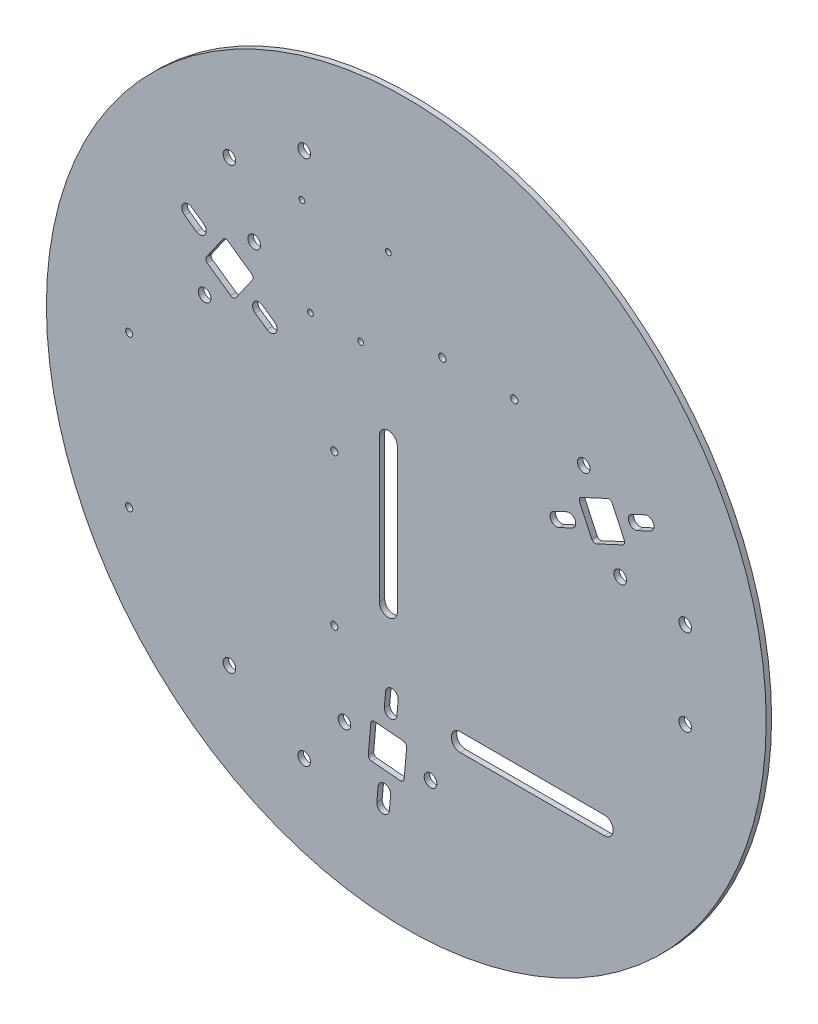
SolidWorks part; units mm, degrees
ref_plane "Front Plane" through (0, 0, 0) normal (0, 0, 1) x (1, 0, 0)
ref_plane "Top Plane" through (0, 0, 0) normal (0, 1, 0) x (1, 0, 0)
ref_plane "Right Plane" through (0, 0, 0) normal (1, 0, 0) x (0, 0, -1)
sketch "Sketch1" plane through (0, 0, 0) normal (0, 0, 1) x (1, 0, 0)
  line L0 (0, 0) -> (-173.2051, 100) construction
  line L1 (0, 0) -> (173.2051, 100) construction
  line L2 (0, 0) -> (0, -200) construction
  line L3 (0, 0) -> (0, 200) construction
  circle A0 centre (0, 0) radius 200
  dimension "D1" = 400
  dimension "D2" = 120
  dimension "D3" = 120
extrude "Boss-Extrude2" add sketch "Sketch1" along normal blind 3
sketch "Sketch9" plane through (0, 0, 3) normal (0, 0, 1) x (1, 0, 0)
  line L0 (0, 0) -> (0, 183.2614) construction
  line L1 (-98.2846, 122.2339) -> (-56.7154, 146.2339) construction
  line L2 (0, 0) -> (-115, 199.1858) construction
  circle A2 centre (-56.7154, 146.2339) radius 3.5
  circle A5 centre (-98.2846, 122.2339) radius 3.5
  point P4 (-77.5, 134.2339)
  dimension "D3" = 7
  dimension "D2" = 24
  dimension "D4" = 155
  dimension "D11" = 30
extrude "Cut-Extrude8" cut sketch "Sketch9" against normal up to surface (3 mm away) up to face at (200, 0, 0)
pattern_circular "CirPattern5" count 3 over 360 about axis through (0, 0, 0) along (0, 0, 1) of "Cut-Extrude8"
sketch "Sketch15" plane through (0, 0, 3) normal (0, 0, 1) x (1, 0, 0)
  line L0 (0, 0) -> (383.7878, 0) construction
  circle A0 centre (20, 85) radius 2
  circle A1 centre (60, 85) radius 2
  dimension "D1" = 4
  dimension "D2" = 4
  dimension "D3" = 40
  dimension "D4" = 85
  dimension "D5" = 20
extrude "Cut-Extrude13" cut sketch "Sketch15" against normal up to surface (3 mm away) up to face at (-53.2154, -146.2339, 0)
sketch "Sketch17" plane through (0, 0, 3) normal (0, 0, 1) x (1, 0, 0)
  line L0 (0, 0) -> (0, 260.2561) construction
  line L1 (0, 0) -> (-189.8731, 132.9506) construction
  line L3 (-112.2255, 66.3734) -> (-95.8425, 54.9019)
  line L5 (-100.754, 82.7565) -> (-84.371, 71.2849)
  line L6 (-112.2255, 66.3734) -> (-100.754, 82.7565)
  line L7 (-95.8425, 54.9019) -> (-84.371, 71.2849)
  line L8 (-81.9152, 57.3576) -> (-75.362, 52.769) construction
  line L9 (-79.9077, 60.2247) -> (-73.3545, 55.6361)
  line L10 (-83.9227, 54.4906) -> (-77.3695, 49.902)
  line L11 (-104.034, 60.6377) -> (-90.1792, 80.4244) construction
  line L12 (-114.6813, 80.3007) -> (-121.2345, 84.8893) construction
  line L13 (-112.6738, 83.1677) -> (-119.227, 87.7563)
  line L14 (-116.6888, 77.4337) -> (-123.242, 82.0223)
  arc A0 (-79.9077, 60.2247) -> (-83.9227, 54.4906) centre (-81.9152, 57.3576) ccw
  arc A1 (-77.3695, 49.902) -> (-73.3545, 55.6361) centre (-75.362, 52.769) ccw
  circle A2 centre (-84.5324, 88.4888) radius 3.5
  circle A3 centre (-112.0641, 49.1695) radius 3.5
  arc A4 (-112.6738, 83.1677) -> (-116.6888, 77.4337) centre (-114.6813, 80.3007) cw
  arc A5 (-123.242, 82.0223) -> (-119.227, 87.7563) centre (-121.2345, 84.8893) cw
  circle A6 centre (-56.7154, 146.2339) radius 3.5 construction
  circle A7 centre (-98.2846, 122.2339) radius 3.5 construction
  circle A8 centre (-56.7154, 146.2339) radius 3.5
  circle A9 centre (-98.2846, 122.2339) radius 3.5
  point P7 (-78.6386, 55.0633)
  point P17 (-80.6461, 52.1963)
  point P24 (-117.9579, 82.595)
  dimension "D9" = 7
  dimension "D1" = 20
  dimension "D2" = 20
  dimension "D3" = 20
  dimension "D4" = 55
  dimension "D5" = 110
  dimension "D6" = 7
  dimension "D7" = 8
  dimension "D8" = 10
  dimension "D10" = 14
  dimension "D11" = 10
extrude "Cut-Extrude15" cut sketch "Sketch17" against normal up to surface (3 mm away) up to face at (22, 85, 0)
pattern_circular "CirPattern7" count 3 over 360 about axis through (0, 0, 0) along (0, 0, 1) of "Cut-Extrude15"
sketch "Sketch18" plane through (0, 0, 3) normal (0, 0, 1) x (1, 0, 0)
  line L0 (-10, 30) -> (-10, -50) construction
  line L1 (-5, 30) -> (-5, -50)
  line L2 (-15, 30) -> (-15, -50)
  arc A0 (-5, 30) -> (-15, 30) centre (-10, 30) ccw
  arc A1 (-15, -50) -> (-5, -50) centre (-10, -50) ccw
  point P2 (-10, -10)
  dimension "D1" = 10
  dimension "D2" = 10
  dimension "D3" = 80
  dimension "D4" = 5
extrude "Cut-Extrude16" cut sketch "Sketch18" against normal up to surface (3 mm away) up to face at (-8.367, -95.6347, 0)
sketch "Sketch19" plane through (0, 0, 3) normal (0, 0, 1) x (1, 0, 0)
  line L0 (0, 0) -> (269.2588, 0) construction
  line L1 (30, -95) -> (110, -95) construction
  line L2 (30, -90) -> (110, -90)
  line L3 (30, -100) -> (110, -100)
  arc A0 (30, -90) -> (30, -100) centre (30, -95) ccw
  arc A1 (110, -100) -> (110, -90) centre (110, -95) ccw
  point P5 (70, -95)
  dimension "D1" = 10
  dimension "D2" = 80
  dimension "D3" = 95
  dimension "D4" = 30
extrude "Cut-Extrude17" cut sketch "Sketch19" against normal up to surface (3 mm away) up to face at (-10, -10, 0)
sketch "Sketch20" plane through (0, 0, 3) normal (0, 0, 1) x (1, 0, 0)
  circle A0 centre (-57.9874, 121.9) radius 1.6
  circle A1 centre (-10, 120.8) radius 1.6
  circle A2 centre (-53.2874, 70) radius 1.6
  circle A3 centre (-25.3874, 70) radius 1.6
  circle A4 centre (20, 85) radius 2 construction
  dimension "D1" = 3.2
  dimension "D2" = 3.2
  dimension "D3" = 3.2
  dimension "D4" = 3.2
  dimension "D5" = 48
  dimension "D6" = 27.9
  dimension "D7" = 4.7
  dimension "D8" = 51.9
  dimension "D9" = 70
  dimension "D10" = 30
  dimension "D11" = 50.8
extrude "Cut-Extrude18" cut sketch "Sketch20" against normal up to surface (3 mm away) up to face at (70, -95, 0)
fillet "Fillet1" radius 2 12 edges at (113.5938, 64.0035, 1.5) (122.0462, 45.8773, 1.5) (95.4677, 55.5511, 1.5) (103.92, 37.4249, 1.5) (-19.5491, -108.7099, 1.5) (-21.2922, -128.6338, 1.5) (0.3748, -110.453, 1.5) (-1.3683, -130.3769, 1.5) (-84.371, 71.2849, 1.5) (-100.754, 82.7565, 1.5) (-112.2255, 66.3734, 1.5) (-95.8425, 54.9019, 1.5)
sketch "Sketch21" plane through (0, 0, 3) normal (0, 0, 1) x (1, 0, 0)
  line L0 (0, 0) -> (-200, 0) construction
  line L1 (-154, 10) -> (-40, 10) construction
  line L2 (-154, -74) -> (-40, -74) construction
  circle A0 centre (0, 0) radius 200 construction
  circle A1 centre (-154, 10) radius 2
  circle A2 centre (-40, 10) radius 2
  circle A3 centre (-154, -74) radius 2
  circle A4 centre (-40, -74) radius 2
  dimension "D1" = 4
  dimension "D2" = 4
  dimension "D3" = 4
  dimension "D4" = 4
  dimension "D5" = 114
  dimension "D6" = 84
  dimension "D7" = 10
  dimension "D8" = 40
  dimension "D9" = 114
extrude "Cut-Extrude19" cut sketch "Sketch21" against normal up to surface (3 mm away) up to face at (-56.3874, 121.9, 0)
